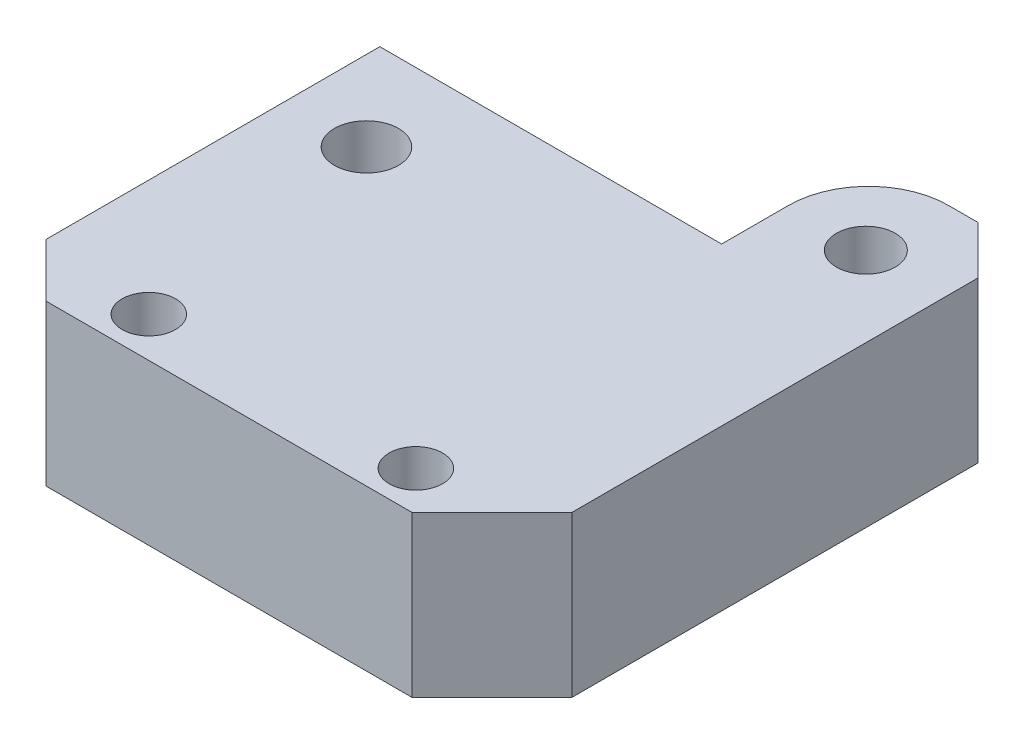
SolidWorks part; units mm, degrees
ref_plane "Front Plane" through (0, 0, 0) normal (0, 0, 1) x (1, 0, 0)
ref_plane "Top Plane" through (0, 0, 0) normal (0, 1, 0) x (1, 0, 0)
ref_plane "Right Plane" through (0, 0, 0) normal (1, 0, 0) x (0, 0, -1)
ref_plane "Plane1" through (0, 6, 0) normal (0, 1, 0) x (1, 0, 0)
sketch "Sketch1" plane through (0, 6, 0) normal (0, 1, 0) x (1, 0, 0)
  line L0 (16.9, -120) -> (0, -120)
  line L1 (0, -120) -> (0, -140)
  line L2 (0, -140) -> (18.7, -140)
  line L3 (18.7, -140) -> (18.7, -121.8)
  line L4 (18.7, -121.8) -> (16.9, -120)
extrude "Boss-Extrude1" add sketch "Sketch1" against normal blind 6
sketch "Sketch2" plane through (0, 0, 0) normal (0, -1, 0) x (1, 0, 0)
  line L0 (0, 120) -> (12.8, 120)
  line L1 (12.8, 120) -> (12.8, 125.1)
  line L2 (12.8, 125.1) -> (0, 125.1)
  line L3 (0, 125.1) -> (0, 120)
extrude "Cut-Extrude1" cut sketch "Sketch2" against normal through all
hole_wizard "#1 Clearance Hole1" positions "Sketch4" profile "Sketch3" hole size "#1" standard "ANSI Inch"
sketch "Sketch4" plane through (0, 6, 0) normal (0, 1, 0) x (1, 0, 0)
  point P0 (14.35, -138.5)
  point P1 (4.35, -138.5)
sketch "Sketch3" plane through (14.35, 6, 138.5) normal (1, 0, 0) x (0, 0, 1)
  line L0 (0, 0) -> (0, 6)
  line L1 (0, 6) -> (1, 6)
  line L2 (1, 6) -> (1, 0)
  line L5 (1, 0) -> (0, 0)
  line L11 (0, -6.35) -> (0, 107.95) construction
  dimension "Thru Hole Dia." = 2
  dimension "Thru Hole Depth" = 6
hole_wizard "#2 Clearance Hole1" positions "Sketch6" profile "Sketch5" hole size "#2" standard "ANSI Inch"
sketch "Sketch6" plane through (0, 6, 0) normal (0, 1, 0) x (1, 0, 0)
  point P0 (3, -129)
sketch "Sketch5" plane through (3, 6, 129) normal (1, 0, 0) x (0, 0, 1)
  line L0 (0, 0) -> (0, 6)
  line L1 (0, 6) -> (1.2, 6)
  line L2 (1.2, 6) -> (1.2, 0)
  line L5 (1.2, 0) -> (0, 0)
  line L11 (0, -6.35) -> (0, 107.95) construction
  dimension "Thru Hole Dia." = 2.4
  dimension "Thru Hole Depth" = 6
hole_wizard "#1 Clearance Hole2" positions "Sketch8" profile "Sketch7" hole size "#1" standard "ANSI Inch"
sketch "Sketch8" plane through (0, 6, 0) normal (0, 1, 0) x (1, 0, 0)
  point P0 (15.7, -123)
sketch "Sketch7" plane through (15.7, 6, 123) normal (1, 0, 0) x (0, 0, 1)
  line L0 (0, 0) -> (0, 6)
  line L1 (0, 6) -> (1.1, 6)
  line L2 (1.1, 6) -> (1.1, 0)
  line L5 (1.1, 0) -> (0, 0)
  line L11 (0, -6.35) -> (0, 107.95) construction
  dimension "Thru Hole Dia." = 2.2
  dimension "Thru Hole Depth" = 6
chamfer "Chamfer1" distance 0.4 angle 45 2 edges at (6.4, 6, 125.1) (6.4, 0, 125.1)
chamfer "Chamfer2" distance 3 angle 45 1 edges at (18.7, 3, 140)
chamfer "Chamfer3" distance 2 angle 45 1 edges at (0, 3, 140)
fillet "Fillet1" radius 3 1 edges at (12.8, 3, 120)
